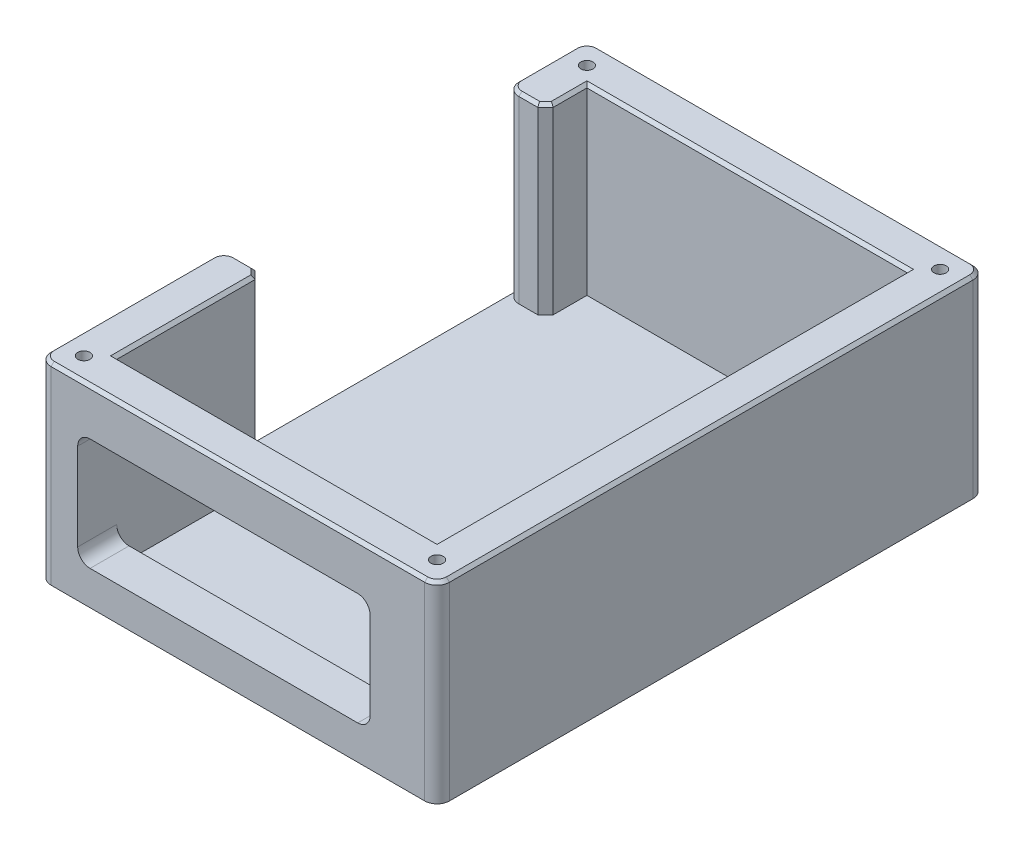
SolidWorks part; units mm, degrees
ref_plane "Front Plane" through (0, 0, 0) normal (0, 0, 1) x (1, 0, 0)
ref_plane "Top Plane" through (0, 0, 0) normal (0, 1, 0) x (1, 0, 0)
ref_plane "Right Plane" through (0, 0, 0) normal (1, 0, 0) x (0, 0, -1)
sketch "Sketch1" plane through (0, 0, 0) normal (0, 1, 0) x (1, 0, 0)
  line L16 (23.3295, 116.7563) -> (105.0795, 116.7563)
  line L17 (31.3295, 108.7563) -> (97.0795, 108.7563) construction
  line L18 (31.3295, 108.7563) -> (31.3295, 12.2563) construction
  line L19 (31.3295, 12.2563) -> (97.0795, 12.2563) construction
  line L20 (97.0795, 108.7563) -> (97.0795, 12.2563) construction
  line L21 (105.0795, 116.7563) -> (105.0795, 4.2563)
  line L22 (23.3295, 4.2563) -> (105.0795, 4.2563)
  line L23 (23.3295, 116.7563) -> (23.3295, 4.2563)
  dimension "D1" = 65.75
  dimension "D2" = 96.5
  dimension "D3" = 8
extrude "Boss-Extrude3" add sketch "Sketch1" along normal blind 39.5
shell "Shell1" thickness 8
sketch "Sketch2" plane through (23.3295, 0, 0) normal (-1, 0, 0) x (0, 0, 1)
  line L0 (-116.7563, 39.5) -> (-4.2563, 39.5) construction
  line L1 (-100.2563, 39.5) -> (-42.2563, 39.5)
  line L2 (-100.2563, 39.5) -> (-100.2563, 2)
  line L3 (-100.2563, 2) -> (-42.2563, 2)
  line L4 (-42.2563, 39.5) -> (-42.2563, 2)
  line L5 (-108.7563, 39.5) -> (-108.7563, 2) construction
  line L9 (-108.7563, 2) -> (-12.2563, 2) construction
  point P8 (-108.7563, 20.75)
  dimension "D1" = 58
  dimension "D2" = 8.5
extrude "Cut-Extrude1" cut sketch "Sketch2" against normal up to next
sketch "Sketch3" plane through (0, 0, -4.2563) normal (0, 0, 1) x (1, 0, 0)
  line L0 (31.3295, 39.5) -> (31.3295, 2) construction
  line L1 (31.3295, 30) -> (91.3295, 30)
  line L2 (31.3295, 30) -> (31.3295, 7)
  line L3 (31.3295, 7) -> (91.3295, 7)
  line L4 (91.3295, 30) -> (91.3295, 7)
  line L5 (31.3295, 2) -> (97.0795, 2) construction
  dimension "D1" = 60
  dimension "D2" = 23
  dimension "D3" = 5
extrude "Cut-Extrude2" cut sketch "Sketch3" against normal up to next
fillet "Fillet1" radius 2.54 6 edges at (23.3295, 20.75, -42.2563) (23.3295, 20.75, -100.2563) (23.3295, 19.75, -116.7563) (23.3295, 19.75, -4.2563) (105.0795, 19.75, -4.2563) (105.0795, 19.75, -116.7563)
chamfer "Chamfer1" distance 1.5875 angle 45 2 edges at (31.3295, 20.75, -42.2563) (31.3295, 20.75, -100.2563)
fillet "Fillet2" radius 2.54 4 edges at (91.3295, 7, -8.2563) (31.3295, 7, -8.2563) (31.3295, 30, -8.2563) (91.3295, 30, -8.2563)
chamfer "Chamfer2" distance 0.635 angle 45 20 edges at (64.2045, 39.5, -12.2563) (97.0795, 39.5, -60.5063) (64.2045, 39.5, -108.7563) (31.3295, 39.5, -105.3001) (30.5357, 39.5, -101.0501) (27.8057, 39.5, -100.2563) (24.0734, 39.5, -101.0003) (23.3295, 39.5, -108.5063) (24.0734, 39.5, -116.0124) (64.2045, 39.5, -116.7563) (104.3355, 39.5, -116.0124) (105.0795, 39.5, -60.5063) (104.3355, 39.5, -5.0003) (64.2045, 39.5, -4.2563) (24.0734, 39.5, -5.0003) (23.3295, 39.5, -23.2563) (24.0734, 39.5, -41.5124) (27.8057, 39.5, -42.2563) (30.5357, 39.5, -41.4626) (31.3295, 39.5, -26.4626)
sketch "Sketch4" plane through (0, 39.5, 0) normal (0, 1, 0) x (1, 0, 0)
  line L0 (102.5395, 116.1213) -> (25.8695, 116.1213) construction
  line L1 (23.9645, 114.2163) -> (23.9645, 102.7963) construction
  line L3 (25.8695, 4.8913) -> (102.5395, 4.8913) construction
  line L5 (104.4445, 6.7963) -> (104.4445, 114.2163) construction
  circle A0 centre (27.9645, 112.1213) radius 1.25
  circle A1 centre (100.4445, 112.1213) radius 1.25
  circle A2 centre (27.9645, 8.8913) radius 1.25
  circle A3 centre (100.4445, 8.8913) radius 1.25
  dimension "D1" = 2.5
  dimension "D2" = 4
  dimension "D3" = 4
  dimension "D4" = 4
  dimension "D5" = 4
extrude "Cut-Extrude3" cut sketch "Sketch4" against normal blind 6.35
equation "\"D5@Sketch4\"=\"D3@Sketch4\""
equation "\"D4@Sketch4\"=\"D2@Sketch4\""
